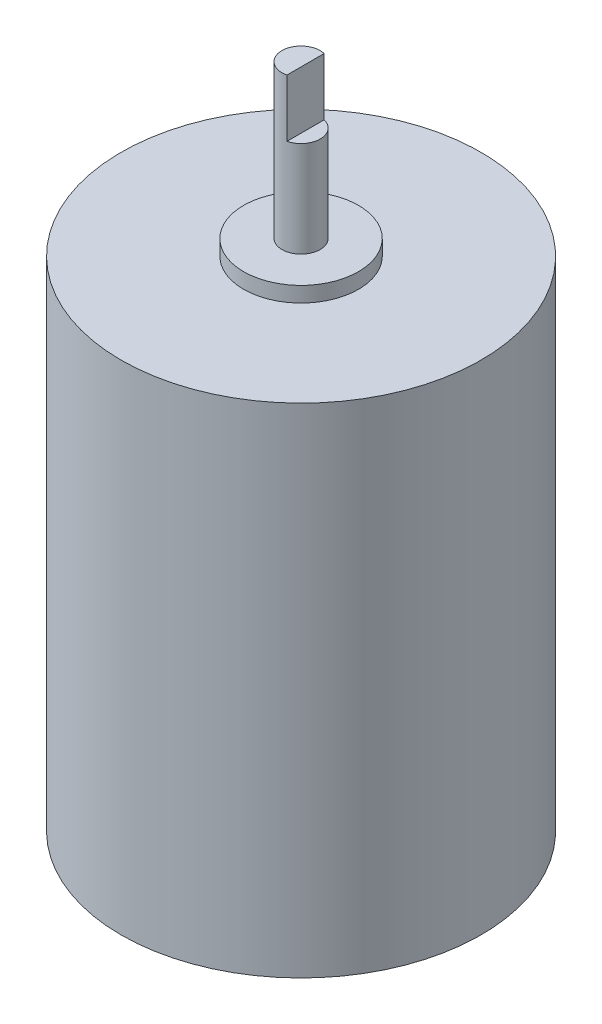
SolidWorks part; units mm, degrees
ref_plane "Front Plane" through (0, 0, 0) normal (0, 0, 1) x (1, 0, 0)
ref_plane "Top Plane" through (0, 0, 0) normal (0, 1, 0) x (1, 0, 0)
ref_plane "Right Plane" through (0, 0, 0) normal (1, 0, 0) x (0, 0, -1)
sketch "Sketch1" plane through (0, 0, 0) normal (0, 1, 0) x (1, 0, 0)
  circle A0 centre (0, 0) radius 23.5
extrude "Boss-Extrude1" add sketch "Sketch1" along normal blind 65
sketch "Sketch2" plane through (0, 65, 0) normal (0, 1, 0) x (1, 0, 0)
  circle A0 centre (0, 0) radius 7.5
extrude "Boss-Extrude2" add sketch "Sketch2" along normal blind 2
sketch "Sketch3" plane through (0, 67, 0) normal (0, 1, 0) x (1, 0, 0)
  circle A0 centre (0, 0) radius 2.5
extrude "Boss-Extrude3" add sketch "Sketch3" along normal blind 20
sketch "Sketch4" plane through (0, 87, 0) normal (0, 1, 0) x (1, 0, 0)
  line L0 (0.592, 2.4289) -> (0.592, -2.4289)
  arc A0 (0.592, 2.4289) -> (0.592, -2.4289) centre (0, 0) cw
  circle A1 centre (0, 0) radius 2.5 construction
extrude "Cut-Extrude2" cut sketch "Sketch4" against normal blind 7.5
